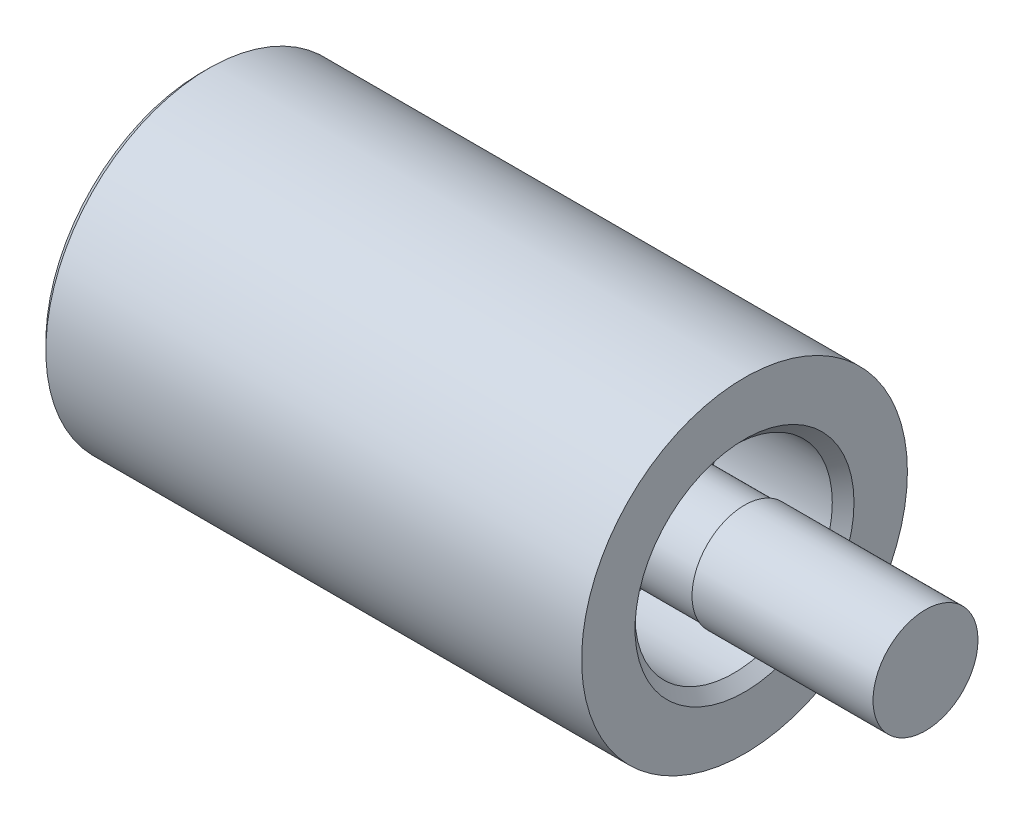
SolidWorks part; units mm, degrees
ref_plane "前视基准面" through (0, 0, 0) normal (0, 0, 1) x (1, 0, 0)
ref_plane "上视基准面" through (0, 0, 0) normal (0, 1, 0) x (1, 0, 0)
ref_plane "右视基准面" through (0, 0, 0) normal (1, 0, 0) x (0, 0, -1)
other "Configuration Table"
sketch "草图1" plane through (0, 0, 0) normal (1, 0, 0) x (0, 0, -1)
  line L0 (-2.2, 4.4) -> (2.2, 4.4)
  line L1 (-2.2, -8) -> (2.2, -8) construction
  line L2 (-2.2, -8) -> (-2.2, -6.8557) construction
  line L3 (-2.2, 8) -> (2.2, 8) construction
  line L4 (2.2, -8) -> (2.2, -6.8557) construction
  line L5 (-1.9091, -6.9423) -> (1.9091, 6.9423) construction
  line L6 (-1.9091, 6.9423) -> (1.9091, -6.9423) construction
  line L7 (2.2, -6.8557) -> (2.2, 4.4) construction
  line L8 (2.2, 4.4) -> (2.2, 6.8557)
  line L9 (-2.2, -6.8557) -> (-2.2, 4.4) construction
  line L10 (-2.2, 4.4) -> (-2.2, 6.8557)
  line L11 (1.9091, -6.9423) -> (2.2, -8) construction
  line L12 (-2.2, -8) -> (-1.9091, -6.9423) construction
  line L13 (2.2, 6.8557) -> (2.2, 8) construction
  line L14 (1.9091, 6.9423) -> (2.2, 8) construction
  line L15 (-2.2, 8) -> (-1.9091, 6.9423) construction
  line L16 (-2.2, 6.8557) -> (-2.2, 8) construction
  circle A0 centre (0, 0) radius 9
  arc A1 (-2.2, 6.8557) -> (2.2, 6.8557) centre (0, 0) ccw
  arc A2 (1.9091, 6.9423) -> (-1.9091, 6.9423) centre (0, 0) ccw construction
  arc A3 (2.2, 6.8557) -> (1.9091, 6.9423) centre (0, 0) ccw construction
  arc A4 (-1.9091, 6.9423) -> (-2.2, 6.8557) centre (0, 0) ccw construction
  dimension "D1" = 18
  dimension "D2" = 14.4
  dimension "D3" = 4.4
  dimension "D4" = 16
  dimension "D5" = 3.6
extrude "凸台-拉伸1" add sketch "草图1" against normal blind 20
sketch "草图2" plane through (0, 0, 0) normal (1, 0, 0) x (0, 0, -1)
  circle A0 centre (0, 0) radius 9
  dimension "D1" = 18
extrude "凸台-拉伸2" add sketch "草图2" along normal blind 10
sketch "草图4" plane through (10, 0, 0) normal (1, 0, 0) x (0, 0, -1)
  circle A0 centre (0, 0) radius 5.45
  circle A1 centre (0, 0) radius 2.8
  dimension "D1" = 10.9
  dimension "D2" = 5.6
extrude "切除-拉伸1" cut sketch "草图4" against normal blind 7
sketch "草图5" plane through (10, 0, 0) normal (1, 0, 0) x (0, 0, -1)
  circle A0 centre (0, 0) radius 2.9
  dimension "D1" = 5.8
extrude "凸台-拉伸3" add sketch "草图5" along normal blind 10
fillet "圆角1" radius 0.6 1 edges at (10, 0, -5.45) profile chamfer
fillet "圆角2" radius 0.4 5 edges at (-20, 0, -9) (-20, 5.6278, 2.2) (-20, -7.2, 0) (-20, 5.6278, -2.2) (-20, 4.4, 0) profile chamfer
fillet "圆角3" radius 0.4 2 edges at (-9.8, 4.4, -2.2) (-9.8, 4.4, 2.2)
